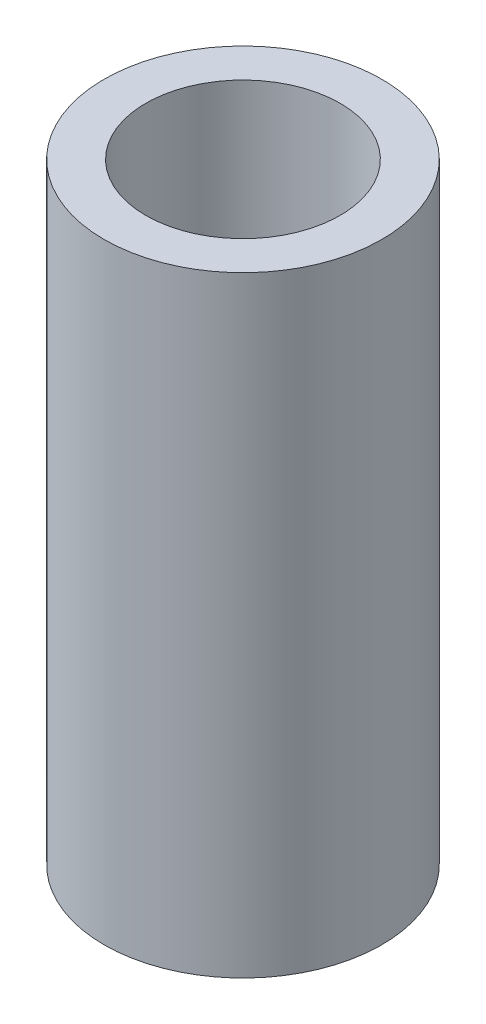
SolidWorks part; units mm, degrees
material "6061 Alloy"
ref_plane "Front Plane" through (0, 0, 0) normal (0, 0, 1) x (1, 0, 0)
ref_plane "Top Plane" through (0, 0, 0) normal (0, 1, 0) x (1, 0, 0)
ref_plane "Right Plane" through (0, 0, 0) normal (1, 0, 0) x (0, 0, -1)
sketch "Sketch1" plane through (0, 0, 0) normal (0, 1, 0) x (1, 0, 0)
  circle A0 centre (0, 0) radius 2.5
  circle A1 centre (0, 0) radius 1.75
  dimension "D1" = 5
  dimension "D2" = 3.5
extrude "Boss-Extrude1" add sketch "Sketch1" along normal blind 11
